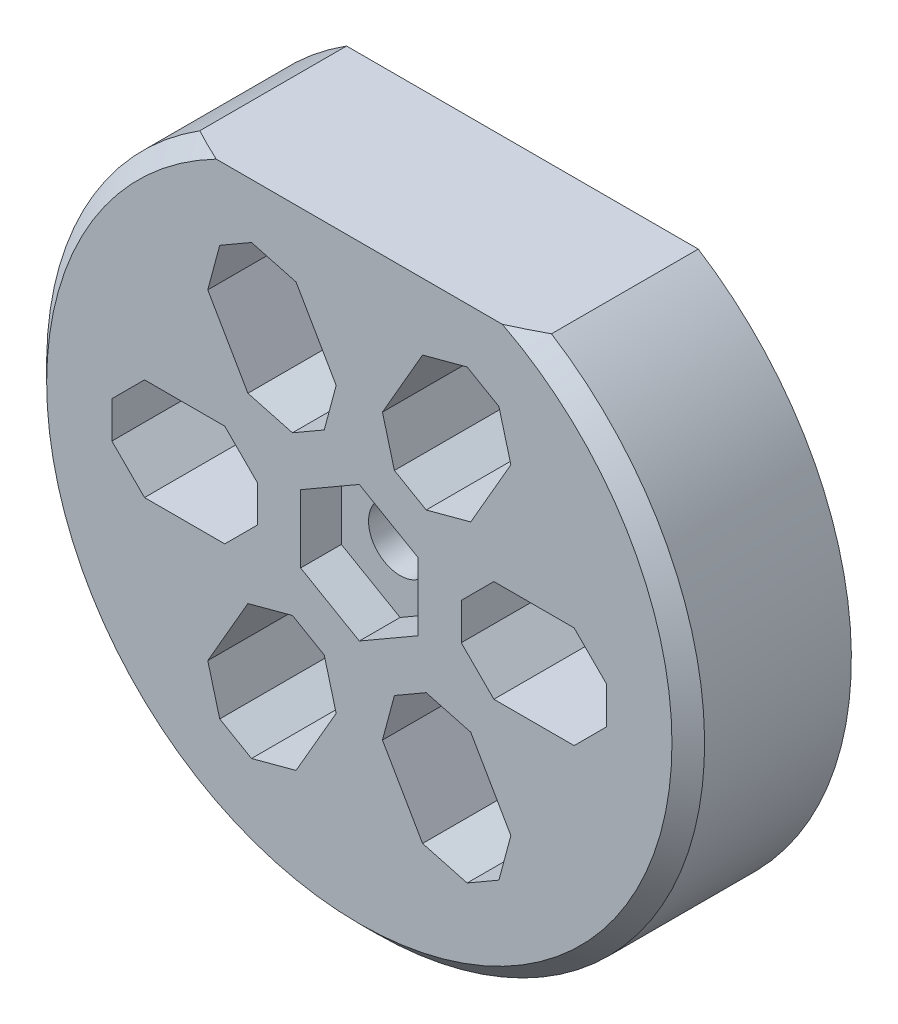
SolidWorks part; units mm, degrees
material "PET"
ref_plane "Front Plane" through (0, 0, 0) normal (0, 0, 1) x (1, 0, 0)
ref_plane "Top Plane" through (0, 0, 0) normal (0, 1, 0) x (1, 0, 0)
ref_plane "Right Plane" through (0, 0, 0) normal (1, 0, 0) x (0, 0, -1)
sketch "Sketch1" plane through (0, 0, 0) normal (0, 0, 1) x (1, 0, 0)
  line L0 (13.6938, 21.6484) -> (-13.6938, 21.6484)
  line L1 (14.8477, 21.6484) -> (21.0029, 21.6484) construction
  arc A0 (-13.6938, 21.6484) -> (13.6938, 21.6484) centre (0, 0) ccw
  dimension "D1" = 51.2318
extrude "Boss-Extrude1" add sketch "Sketch1" along normal blind 12.7
chamfer "Chamfer1" distance 1.27 angle 45 1 edges at (0, -25.6159, 12.7)
sketch "Sketch2" plane through (0, 0, 12.7) normal (0, 0, 1) x (1, 0, 0)
  line L0 (0, -55) -> (0, 55) construction
  line L1 (-4.572, -2.6396) -> (0, -5.2793)
  line L2 (0, -5.2793) -> (4.572, -2.6396)
  line L3 (4.572, -2.6396) -> (4.572, 2.6396)
  line L4 (4.572, 2.6396) -> (0, 5.2793)
  line L5 (0, 5.2793) -> (-4.572, 2.6396)
  line L6 (-4.572, 2.6396) -> (-4.572, -2.6396)
  circle A0 centre (0, 0) radius 4.572 construction
  circle A1 centre (0, 0) radius 25.6159 construction
  dimension "D1" = 9.144
extrude "Cut-Extrude1" cut sketch "Sketch2" against normal blind 3.175
hole_wizard "#8 Clearance Hole1" positions "Sketch3" profile "Sketch4" hole size "#8" standard "ANSI Inch" end condition through all
sketch "Sketch3" plane through (0, 0, 12.7) normal (0, 0, 1) x (1, 0, 0)
  point P0 (0, 0)
sketch "Sketch4" plane through (0, 0, 12.7) normal (1, 0, 0) x (0, -1, 0)
  line L0 (0, 0) -> (0, 12.7)
  line L1 (0, 12.7) -> (2.4574, 12.7)
  line L2 (2.4574, 12.7) -> (2.4574, 0)
  line L5 (2.4574, 0) -> (0, 0)
  line L11 (0, -6.35) -> (0, 107.95) construction
  dimension "Thru Hole Dia." = 4.9149
  dimension "Thru Hole Depth" = 12.7
sketch "Sketch5" plane through (0, 0, 12.7) normal (0, 0, 1) x (1, 0, 0)
  line L0 (-2.286, -3.9595) -> (-3.9687, -6.8741) construction
  line L1 (-4.572, -2.6396) -> (0, -5.2793) construction
  line L2 (-3.9687, -6.8741) -> (-9.6329, -16.6848)
  line L3 (-4.572, 0) -> (-7.9375, 0) construction
  line L4 (-4.572, 2.6396) -> (-4.572, -2.6396) construction
  line L5 (-7.9375, 0) -> (-19.2659, 0)
  line L6 (-2.286, 3.9595) -> (-3.9687, 6.8741) construction
  line L7 (0, 5.2793) -> (-4.572, 2.6396) construction
  line L8 (-3.9687, 6.8741) -> (-9.6329, 16.6848)
  line L9 (2.286, 3.9595) -> (3.9687, 6.8741) construction
  line L10 (4.572, 2.6396) -> (0, 5.2793) construction
  line L11 (3.9687, 6.8741) -> (9.6329, 16.6848)
  line L12 (4.572, 0) -> (7.9375, 0) construction
  line L13 (4.572, -2.6396) -> (4.572, 2.6396) construction
  line L14 (7.9375, 0) -> (19.2659, 0)
  line L15 (2.286, -3.9595) -> (3.9688, -6.8741) construction
  line L16 (0, -5.2793) -> (4.572, -2.6396) construction
  line L17 (3.9688, -6.8741) -> (9.633, -16.6848)
  circle A0 centre (0, 0) radius 19.2659 construction
  circle A1 centre (0, 0) radius 7.9375 construction
  circle A2 centre (0, 0) radius 25.6159 construction
  dimension "D1" = 6.35
  dimension "D2" = 15.875
extrude "Cut-Extrude-Thin1" cut sketch "Sketch5" against normal through all thin thin type mid plane wall 7.9375
chamfer "Chamfer2" distance 2.54 angle 45 24 edges at (-13.07, -14.7004, 6.35) (-6.1959, -18.6691, 6.35) (-7.4058, -4.8897, 6.35) (-0.5317, -8.8585, 6.35) (0.5317, -8.8585, 6.35) (6.1959, -18.6691, 6.35) (13.07, -14.7004, 6.35) (7.4058, -4.8897, 6.35) (19.2659, 3.9688, 6.35) (19.2659, -3.9688, 6.35) (7.9375, -3.9688, 6.35) (7.9375, 3.9688, 6.35) (6.1959, 18.6691, 6.35) (0.5317, 8.8585, 6.35) (7.4058, 4.8897, 6.35) (13.07, 14.7004, 6.35) (-13.07, 14.7004, 6.35) (-7.4058, 4.8897, 6.35) (-0.5317, 8.8585, 6.35) (-6.1959, 18.6691, 6.35) (-19.2659, 3.9688, 6.35) (-19.2659, -3.9688, 6.35) (-7.9375, -3.9688, 6.35) (-7.9375, 3.9688, 6.35)
